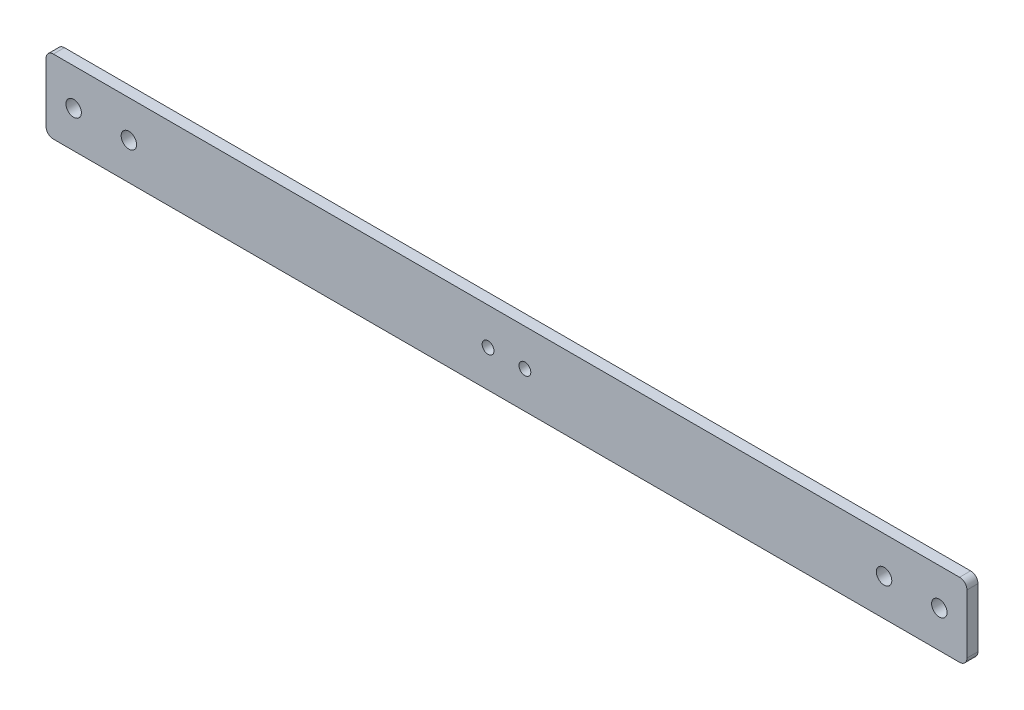
SolidWorks part; units mm, degrees
ref_plane "前视基准面" through (0, 0, 0) normal (0, 0, 1) x (1, 0, 0)
ref_plane "上视基准面" through (0, 0, 0) normal (0, 1, 0) x (1, 0, 0)
ref_plane "右视基准面" through (0, 0, 0) normal (1, 0, 0) x (0, 0, -1)
sketch "草图1" plane through (0, 0, 0) normal (0, 0, 1) x (1, 0, 0)
  line L1 (-125, -10) -> (125, -10)
  line L2 (-125, -10) -> (-125, 10)
  line L3 (-125, 10) -> (125, 10)
  line L4 (125, -10) -> (125, 10)
  line L5 (-125, -10) -> (125, 10) construction
  line L6 (-125, 10) -> (125, -10) construction
  point P0 (0, 0)
  dimension "D1" = 20
  dimension "D2" = 250
extrude "凸台-拉伸1" add sketch "草图1" along normal blind 3
sketch "草图2" plane through (0, 0, 3) normal (0, 0, 1) x (1, 0, 0)
  line L0 (0, 0) -> (50000, 0) construction
  line L1 (-125, 10) -> (-125, -10) construction
  line L2 (0, 0) -> (0, 50000) construction
  circle A0 centre (-117.5, 0) radius 2.1
  circle A1 centre (-102.5, 0) radius 2.1
  circle A2 centre (102.5, 0) radius 2.1
  circle A3 centre (117.5, 0) radius 2.1
  circle A4 centre (-5, 0) radius 1.6
  circle A5 centre (5, 0) radius 1.6
  dimension "D1" = 4.2
  dimension "D2" = 4.2
  dimension "D5" = 3.2
  dimension "D3" = 15
  dimension "D4" = 7.5
  dimension "D6" = 10
extrude "切除-拉伸1" cut sketch "草图2" against normal blind 3
fillet "圆角1" radius 2 4 edges at (125, -10, 1.5) (125, 10, 1.5) (-125, -10, 1.5) (-125, 10, 1.5)
